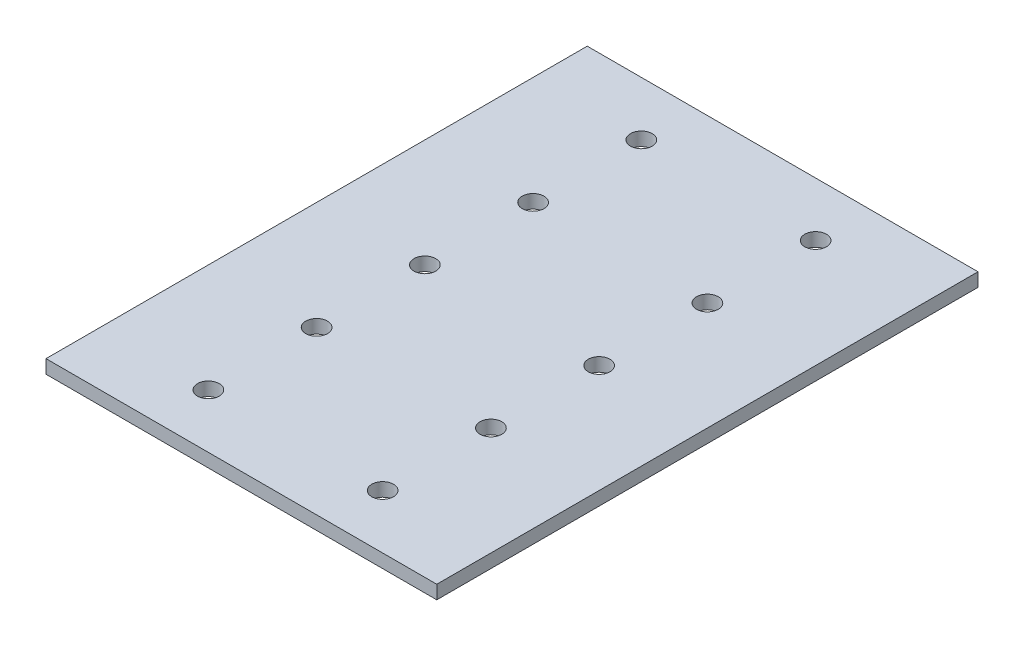
SolidWorks part; units mm, degrees
ref_plane "Front Plane" through (0, 0, 0) normal (0, 0, 1) x (1, 0, 0)
ref_plane "Top Plane" through (0, 0, 0) normal (0, 1, 0) x (1, 0, 0)
ref_plane "Right Plane" through (0, 0, 0) normal (1, 0, 0) x (0, 0, -1)
sketch "Sketch1" plane through (0, 0, 0) normal (0, 1, 0) x (1, 0, 0)
  line L1 (0, 0) -> (91.694, 0)
  line L2 (0, 0) -> (0, 127)
  line L3 (0, 127) -> (91.694, 127)
  line L4 (91.694, 0) -> (91.694, 127)
  dimension "D1" = 91.694
  dimension "D2" = 127
extrude "Boss-Extrude1" add sketch "Sketch1" along normal blind 3.175
sketch "Sketch2" plane through (0, 3.175, 0) normal (0, 1, 0) x (1, 0, 0)
  line L0 (0, 127) -> (0, 0) construction
  line L1 (0, 0) -> (91.694, 0) construction
  circle A0 centre (25.4, 12.7) radius 2.5527
  dimension "D1" = 5.1054
  dimension "D2" = 25.4
  dimension "D3" = 12.7
extrude "Cut-Extrude1" cut sketch "Sketch2" against normal blind 3.175
pattern_linear "LPattern1" count 5 spacing 25.4 along (0, 0, -1) of "Cut-Extrude1"
sketch "Sketch3" plane through (0, 3.175, 0) normal (0, 1, 0) x (1, 0, 0)
  line L0 (91.694, 0) -> (91.694, 127) construction
  line L1 (0, 0) -> (91.694, 0) construction
  circle A0 centre (66.294, 12.7) radius 2.5527
  dimension "D1" = 5.1054
  dimension "D2" = 25.4
  dimension "D3" = 12.7
extrude "Cut-Extrude2" cut sketch "Sketch3" against normal blind 3.175
pattern_linear "LPattern2" count 5 spacing 25.4 along (0, 0, -1) of "Cut-Extrude2"
